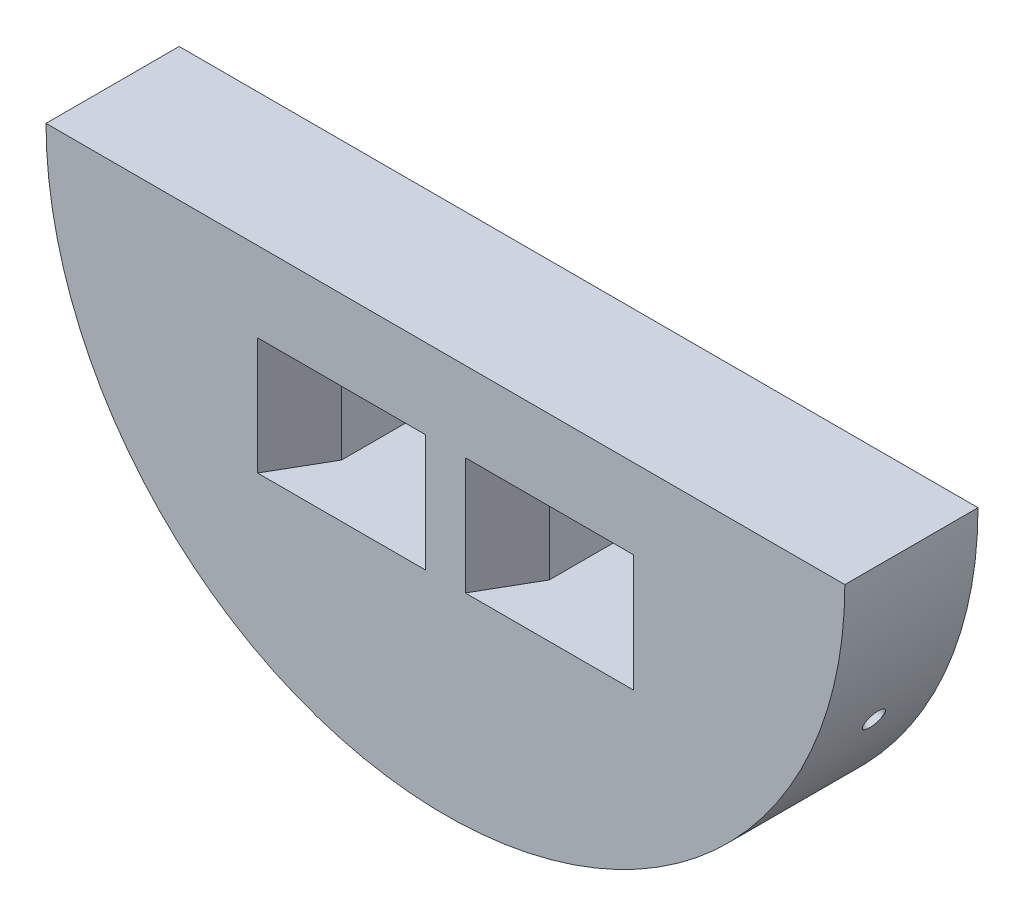
SolidWorks part; units mm, degrees
ref_plane "Front Plane" through (0, 0, 0) normal (0, 0, 1) x (1, 0, 0)
ref_plane "Top Plane" through (0, 0, 0) normal (0, 1, 0) x (1, 0, 0)
ref_plane "Right Plane" through (0, 0, 0) normal (1, 0, 0) x (0, 0, -1)
sketch "Sketch1" plane through (0, 0, 0) normal (0, 0, 1) x (1, 0, 0)
  line L0 (-150, 0) -> (0, 0)
  line L3 (-65.5, -37) -> (-45.5, -37)
  line L4 (-65.5, -37) -> (-65.5, -15)
  line L5 (-65.5, -15) -> (-45.5, -15)
  line L6 (-45.5, -37) -> (-45.5, -15)
  line L7 (-104.5, -37) -> (-84.5, -37)
  line L8 (-104.5, -37) -> (-104.5, -15)
  line L9 (-104.5, -15) -> (-84.5, -15)
  line L10 (-84.5, -37) -> (-84.5, -15)
  arc A1 (-150, 0) -> (0, 0) centre (-75, 0) ccw
  point P0 (-94.5, -15)
  point P13 (-55.5, -15)
  dimension "D1" = 19.5
  dimension "D7" = 75
  dimension "D2" = 15
  dimension "D3" = 19.5
  dimension "D4" = 20
  dimension "D5" = 22
extrude "Boss-Extrude1" add sketch "Sketch1" along normal blind 25
hole_wizard "Ø4.0mm Dowel Hole2" positions "3DSketch2" profile "Sketch4" hole size "Ø4.0" standard "ANSI Metric"
sketch3d "3DSketch2"
  line L2 (0, 0, 25) -> (0, 0, 0) construction
  line L4 (0, 0, 25) -> (0, 0, 0) construction
  line L5 (0, 0, 12.5) -> (-7.0269, -31.6964, 12.5) construction
  line L8 (-75, 0, 0) -> (-75, 0, 25) construction
  line L9 (0, 0, 0) -> (-150, 0, 0) construction
  line L10 (0, 0, 25) -> (-150, 0, 25) construction
  line L12 (-75, 0, 12.5) -> (-7.0269, -31.6964, 12.5) construction
  line L16 (-75, 0, 12.5) -> (0, 0, 12.5) construction
  point P0 (-7.0269, -31.6964, 12.5)
  point P16 (-7.0269, -31.6964, 12.5)
  point P23 (-7.0269, -31.6964, 12.5)
  point P25 (-7.0269, -31.6964, 12.5)
  dimension "D1" = 25
sketch "Sketch4" plane through (-7.0269, -31.6964, 12.5) normal (0, 0, 1) x (0.4226, 0.9063, 0)
  line L0 (0, 0) -> (0, 17.2017)
  line L1 (0, 17.2017) -> (2, 16)
  line L2 (2, 16) -> (2, 0.025)
  line L3 (2, 0.025) -> (2.025, 0)
  line L5 (2.025, 0) -> (0, 0)
  line L6 (-2, 0.025) -> (-2.025, 0) construction
  line L10 (0, 17.2017) -> (-2, 16) construction
  line L11 (0, -6.35) -> (0, 107.95) construction
  dimension "Hole Dia." = 4
  dimension "Hole Depth" = 16
  dimension "Near C'Sink Dia." = 4.05
  dimension "Near C'Sink Angle" = 90
  dimension "Drill Angle" = 118
pattern_circular "CirPattern1" count 5 over 130 about axis through (-75, 0, 0) along (0, 0, 1) of "Ø4.0mm Dowel Hole2"
chamfer "Chamfer1" distance 15 angle 30 2 edges at (-94.5, -15, 0) (-55.5, -15, 0)
chamfer "Chamfer3" distance 10 angle 30 4 edges at (-104.5, -26, 25) (-84.5, -26, 25) (-45.5, -26, 25) (-65.5, -26, 25)
